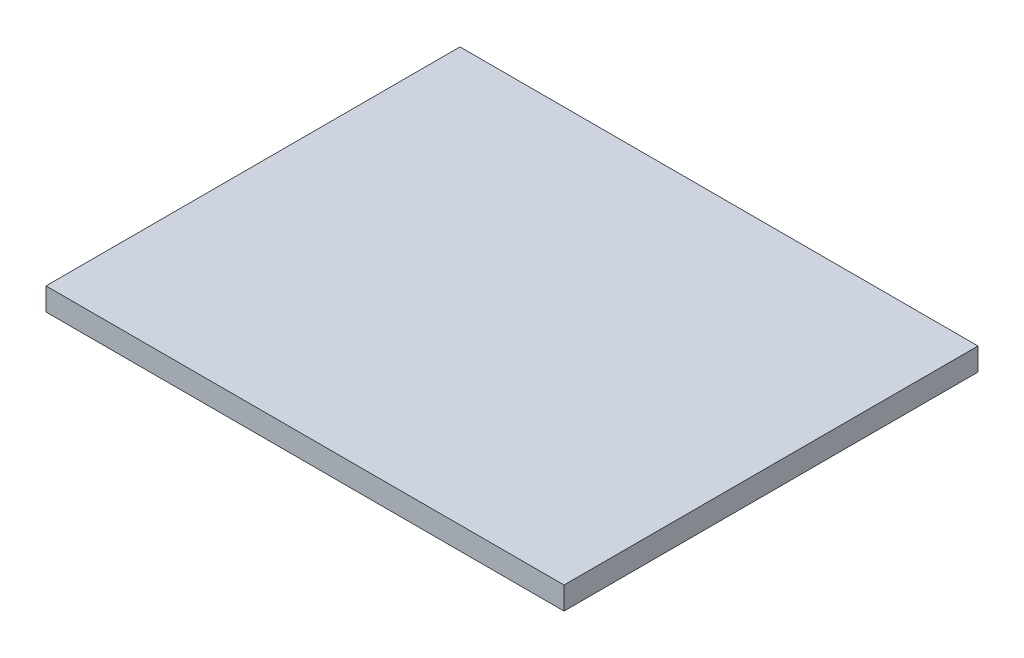
SolidWorks part; units mm, degrees
ref_plane "Front Plane" through (0, 0, 0) normal (0, 0, 1) x (1, 0, 0)
ref_plane "Top Plane" through (0, 0, 0) normal (0, 1, 0) x (1, 0, 0)
ref_plane "Right Plane" through (0, 0, 0) normal (1, 0, 0) x (0, 0, -1)
sketch "Sketch1" plane through (0, 0, 0) normal (0, 1, 0) x (1, 0, 0)
  line L0 (-23.9, 0) -> (21.9, 0) construction
  line L2 (-23.9, 18.3) -> (21.9, 18.3)
  line L3 (-23.9, 18.3) -> (-23.9, -18.3)
  line L4 (-23.9, -18.3) -> (21.9, -18.3)
  line L5 (21.9, 18.3) -> (21.9, -18.3)
  point P7 (21.9, 0)
  point P8 (-23.9, 0)
  dimension "D1" = 36.6
  dimension "D2" = 21.9
  dimension "D3" = 23.9
extrude "Boss-Extrude1" add sketch "Sketch1" along normal blind 2
equation "\"board_w\"= 33.8"
equation "\"board_l\"= 41"
equation "\"stack_h\"= 19.5"
equation "\"module_w\"= 9.9"
equation "\"lens_d\"= 7.8"
equation "\"lens_from_end\"= 8"
equation "\"usb_w\"= 13"
equation "\"plug_h\"= 7"
equation "\"usb_from_back\"= 6"
equation "\"clear\"= 0.4"
equation "\"wall\"= 3"
equation "\"floor_t\"= 2.5"
equation "\"pocket_clear\"= 0.3"
equation "\"lens_clear\"= 0.6"
equation "\"plate_w\"= 16"
equation "\"plate_clear\"= 0.3"
equation "\"plate_t\"= 1.2"
equation "\"plate_seat\"= 0.8"
equation "\"window_d\"= 12"
equation "\"lid_t\"= 2"
equation "\"lid_gap\"= 1"
equation "\"groove_d\"= 1.2"
equation "\"groove_clear\"= 0.15"
equation "\"lip_top\"= 1.2"
equation "\"side_clear\"= 0.2"
equation "\"slide_clear\"= 0.2"
equation "\"ball_d\"= 16"
equation "\"ball_clear\"= 0.3"
equation "\"lip\"= 1.2"
equation "\"cup_floor\"= 1.2"
equation "\"cup_d\"= 26"
equation "\"slit_w\"= 1.5"
equation "\"slit_depth\"= 9"
equation "\"lug_w\"= 16"
equation "\"m3_hole\"= 3.4"
equation "\"m3_nut\"= 5.7"
equation "\"m3_nut_d\"= 2.6"
equation "\"boss_d\"= 20"
equation "\"boss_h\"= 8"
equation "\"nut_af\"= 11.4"
equation "\"nut_t\"= 5.8"
equation "\"screw_hole\"= 6.6"
equation "\"in_l\"= \"board_l\" + 2 * \"clear\""
equation "\"in_w\"= \"board_w\" + 2 * \"clear\""
equation "\"out_l\"= \"in_l\" + 2 * \"wall\""
equation "\"out_w\"= \"in_w\" + 2 * \"wall\""
equation "\"y_groove\"= \"floor_t\" - \"plate_seat\" + \"stack_h\" + \"lid_gap\""
equation "\"groove_h\"= \"lid_t\" + 2 * \"groove_clear\""
equation "\"tray_h\"= \"y_groove\" + \"groove_h\" + \"lip_top\""
equation "\"lid_w\"= \"in_w\" + 2 * \"groove_d\" - 2 * \"side_clear\""
equation "\"lid_right\"= \"in_l\" / 2 + \"groove_d\" - \"slide_clear\""
equation "\"lid_left\"= \"out_l\" / 2"
equation "\"open_d\"= \"ball_d\" - 2 * \"lip\""
equation "\"c_ball\"= sqr( ( ( \"ball_d\" + \"ball_clear\" ) / 2 ) ^ 2 - ( \"open_d\" / 2 ) ^ 2 )"
equation "\"cup_h\"= \"cup_floor\" + ( \"ball_d\" + \"ball_clear\" ) / 2 + \"c_ball\""
equation "\"lug_in\"= \"cup_d\" / 2 - 5"
equation "\"lug_out\"= \"cup_d\" / 2 + 4"
equation "\"D2@Sketch1\"= \"lid_right\""
equation "\"D3@Sketch1\"=\"lid_left\""
equation "\"D1@Boss-Extrude1\"=\"lid_t\""
